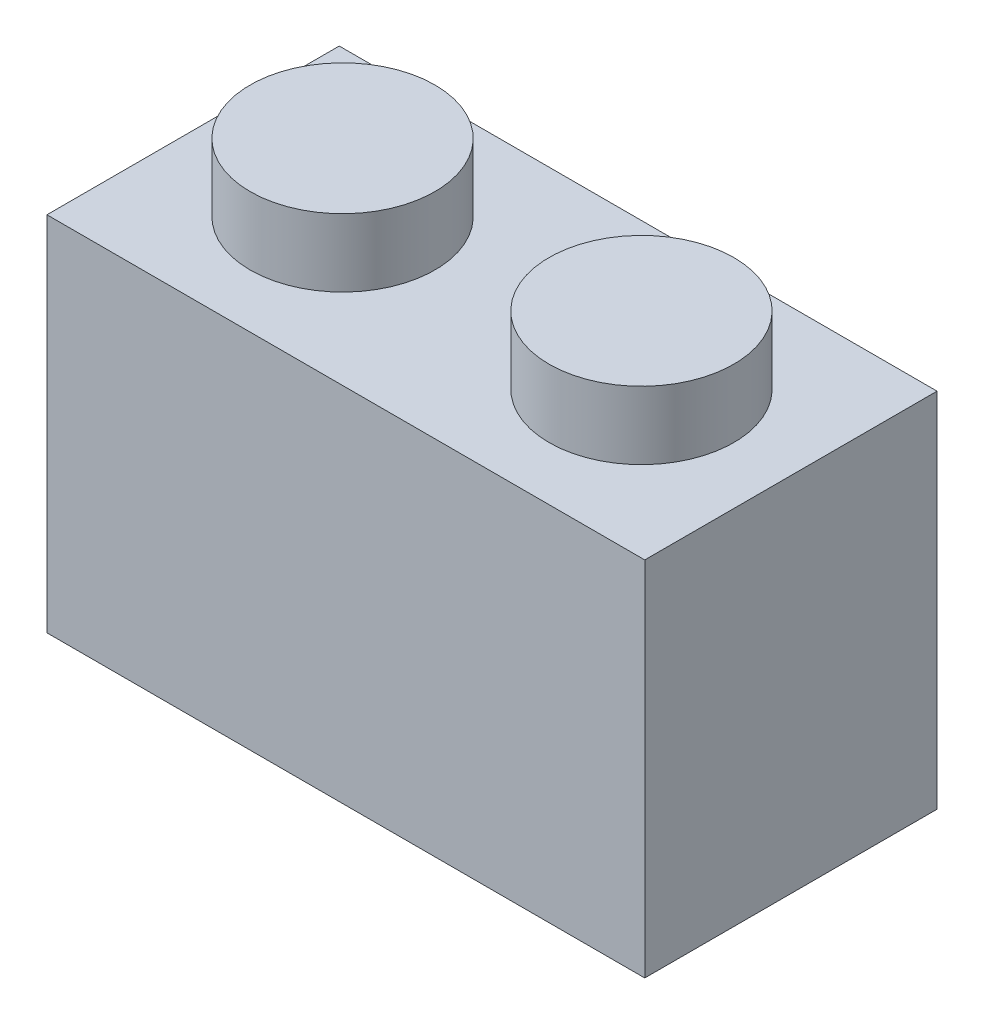
SolidWorks part; units mm, degrees
ref_plane "Front Plane" through (0, 0, 0) normal (0, 0, 1) x (1, 0, 0)
ref_plane "Top Plane" through (0, 0, 0) normal (0, 1, 0) x (1, 0, 0)
ref_plane "Right Plane" through (0, 0, 0) normal (1, 0, 0) x (0, 0, -1)
sketch "Sketch1" plane through (0, 0, 0) normal (0, 1, 0) x (1, 0, 0)
  line L1 (-7.925, 3.875) -> (7.925, 3.875)
  line L2 (-7.925, 3.875) -> (-7.925, -3.875)
  line L3 (-7.925, -3.875) -> (7.925, -3.875)
  line L4 (7.925, 3.875) -> (7.925, -3.875)
  line L5 (-7.925, 3.875) -> (7.925, -3.875) construction
  line L6 (-7.925, -3.875) -> (7.925, 3.875) construction
  point P0 (0, 0)
  dimension "D1" = 15.85
  dimension "D2" = 7.75
extrude "Boss-Extrude1" add sketch "Sketch1" against normal blind 9.6
sketch "Sketch2" plane through (0, 0, 0) normal (0, 1, 0) x (1, 0, 0)
  line L1 (-7.925, 3.875) -> (-7.925, -3.875) construction
  line L2 (-7.925, -3.875) -> (7.925, -3.875) construction
  circle A0 centre (-3.9625, 0) radius 2.45
  circle A1 centre (3.9625, 0) radius 2.45
  dimension "D1" = 3.9625
  dimension "D3" = 4.9
  dimension "D5" = 7.925
  dimension "D2" = 3.875
  dimension "D4" = 2
extrude "Boss-Extrude2" add sketch "Sketch2" along normal blind 1.8
shell "Shell1" thickness 1.5
sketch "Sketch3" plane through (0, -1.5, 0) normal (0, -1, 0) x (1, 0, 0)
  circle A0 centre (0, 0) radius 1.5
  dimension "D1" = 3
extrude "Boss-Extrude3" add sketch "Sketch3" along normal offset from surface (7.9 mm away) 0.2 up to face at (0, -9.6, 0)
